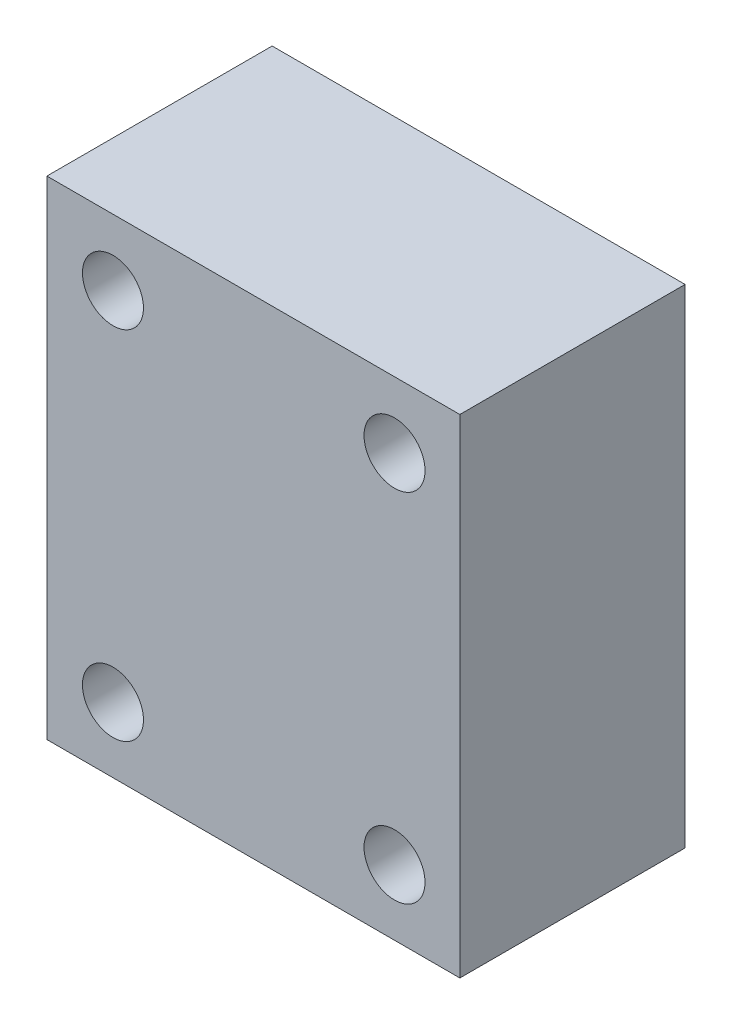
SolidWorks part; units mm, degrees
ref_plane "Front Plane" through (0, 0, 0) normal (1, 0, 0) x (0, 1, 0)
ref_plane "Top Plane" through (0, 0, 0) normal (0, 0, 1) x (0, 1, 0)
ref_plane "Right Plane" through (0, 0, 0) normal (0, 1, 0) x (-1, 0, 0)
sketch "Sketch1" plane through (0, 0, 0) normal (0, 0, 1) x (0, 1, 0)
  line L1 (-41.275, -34.925) -> (41.275, -34.925)
  line L2 (-41.275, -34.925) -> (-41.275, 34.925)
  line L3 (-41.275, 34.925) -> (41.275, 34.925)
  line L4 (41.275, -34.925) -> (41.275, 34.925)
  line L5 (-41.275, -34.925) -> (41.275, 34.925) construction
  line L6 (-41.275, 34.925) -> (41.275, -34.925) construction
  point P0 (0, 0)
extrude "Boss-Extrude1" add sketch "Sketch1" along normal mid plane 38.1
sketch "Sketch2" plane through (0, 0, 0) normal (0, 0, 1) x (0, 1, 0)
  circle A0 centre (-30.226, -23.876) radius 5.1594
extrude "Cut-Extrude2" cut sketch "Sketch2" along normal up to next from offset 19.05
sketch "Sketch3" plane through (0, 0, 0) normal (0, 0, 1) x (0, 1, 0)
  circle A0 centre (30.099, -23.876) radius 5.1594
  circle A1 centre (-30.226, 23.749) radius 5.1594
  circle A2 centre (30.099, 23.749) radius 5.1594
extrude "Cut-Extrude4" cut sketch "Sketch3" along normal up to next from offset 19.05
sketch "Sketch4" plane through (0, 0, 0) normal (0, 0, 1) x (0, 1, 0)
  circle A0 centre (-17.653, 0) radius 7.3422
extrude "Cut-Extrude6" cut sketch "Sketch4" along normal blind 28.448 from offset 19.05
sketch "Sketch5" plane through (0, 0, 0) normal (0, 0, 1) x (0, 1, 0)
  circle A0 centre (-17.653, 0) radius 12.7254
extrude "Cut-Extrude8" cut sketch "Sketch5" along normal blind 2.8194 from offset 19.05
sketch "Sketch6" plane through (0, 0, 0) normal (0, 0, 1) x (0, 1, 0)
  circle A0 centre (17.399, 0) radius 7.3422
extrude "Cut-Extrude10" cut sketch "Sketch6" along normal blind 28.448 from offset 19.05
sketch "Sketch7" plane through (0, 0, 0) normal (0, 0, 1) x (0, 1, 0)
  circle A0 centre (17.399, 0) radius 12.7254
extrude "Cut-Extrude12" cut sketch "Sketch7" along normal blind 2.8194 from offset 19.05
sketch "Sketch8" plane through (0, 0, 0) normal (0, 1, 0) x (-1, 0, 0)
  circle A0 centre (0, 0) radius 7.2152
